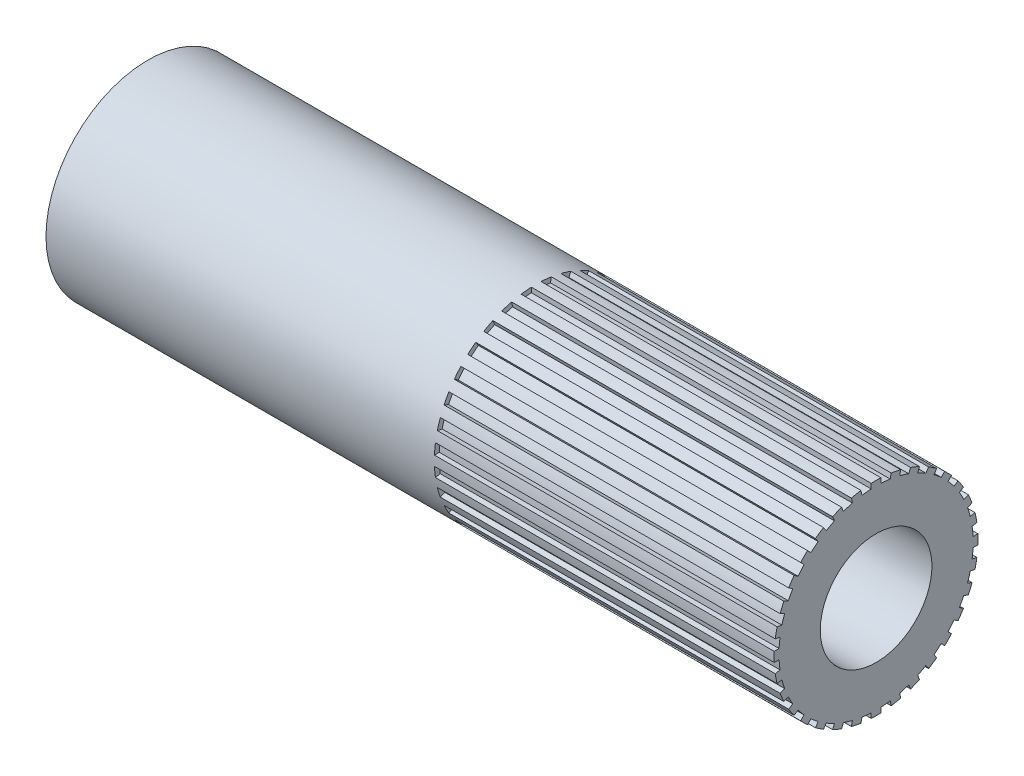
SolidWorks part; units mm, degrees
material "AISI 1020"
ref_plane "Front Plane" through (0, 0, 0) normal (0, 0, 1) x (1, 0, 0)
ref_plane "Top Plane" through (0, 0, 0) normal (0, 1, 0) x (1, 0, 0)
ref_plane "Right Plane" through (0, 0, 0) normal (1, 0, 0) x (0, 0, -1)
sketch "Sketch1" plane through (0, 0, 0) normal (0, 1, 0) x (1, 0, 0)
  line L0 (-77.5, 0) -> (77.5, 0) construction
  line L2 (-77.5, 0) -> (-77.5, -16)
  line L3 (-77.5, -16) -> (77.5, -16)
  line L4 (77.5, 0) -> (77.5, -16)
  line L5 (0, 0) -> (77.5, -16) construction
  line L6 (-77.5, -16) -> (0, 0) construction
  line L7 (-77.5, 0) -> (77.5, 0)
  point P0 (0, 0)
  point P2 (0, 0)
  dimension "D1" = 155
  dimension "D2" = 16
revolve "Revolve1" add sketch "Sketch1" angle 360 about L7
sketch "Sketch2" plane through (0, 0, 0) normal (0, 1, 0) x (1, 0, 0)
  line L1 (-77.5, 16) -> (-77.5, -16) construction
  circle A0 centre (-53.5, 0) radius 6.25
  dimension "D1" = 12.5
  dimension "D2" = 24
extrude "Cut-Extrude1" cut sketch "Sketch2" against normal through all both and the other way through all
sketch "Sketch4" plane through (-77.5, 0, 0) normal (-1, 0, 0) x (0, 0, 1)
  line L1 (-25, 3.5) -> (25, 3.5)
  line L2 (-25, 3.5) -> (-25, -3.5)
  line L3 (-25, -3.5) -> (25, -3.5)
  line L4 (25, 3.5) -> (25, -3.5)
  line L5 (-25, 3.5) -> (25, -3.5) construction
  line L6 (-25, -3.5) -> (25, 3.5) construction
  point P0 (0, 0)
  dimension "D1" = 7
  dimension "D2" = 50
extrude "Cut-Extrude3" cut sketch "Sketch4" against normal blind 38
sketch "Sketch6" plane through (-77.5, 0, 0) normal (-1, 0, 0) x (0, 0, 1)
  line L1 (-15.6125, 3.5) -> (15.6125, 3.5)
  line L2 (-15.6125, 3.5) -> (15.6125, 3.5)
  line L3 (15.6125, -3.5) -> (-15.6125, -3.5)
  line L4 (15.6125, -3.5) -> (-15.6125, -3.5)
  arc A1 (15.6125, 3.5) -> (-15.6125, 3.5) centre (0, 0) ccw
  arc A2 (15.6125, 3.5) -> (-15.6125, 3.5) centre (0, 0) ccw
  arc A3 (-15.6125, -3.5) -> (15.6125, -3.5) centre (0, 0) ccw
  arc A4 (-15.6125, -3.5) -> (15.6125, -3.5) centre (0, 0) ccw
  dimension "D1" = 0
  dimension "D2" = 0
extrude "Boss-Extrude1" add sketch "Sketch6" along normal blind 5
sketch "Sketch7" plane through (-82.5, 0, 0) normal (-1, 0, 0) x (0, 0, 1)
  point P0 (0, 0)
hole_wizard "Ø24.0 (24) Diameter Hole1" positions "Sketch10" profile "Sketch11" hole size "Ø24.0" standard "ANSI Metric"
sketch "Sketch10" plane through (-82.5, 0, 0) normal (-1, 0, 0) x (0, 0, 1)
  point P0 (0, 0)
sketch "Sketch11" plane through (-82.5, 0, 0) normal (0, 1, 0) x (0, 0, 1)
  line L0 (0, 0) -> (0, 27.2103)
  line L1 (0, 27.2103) -> (12, 20)
  line L2 (12, 20) -> (12, 0)
  line L5 (12, 0) -> (0, 0)
  line L10 (0, 27.2103) -> (-12, 20) construction
  line L11 (0, -6.35) -> (0, 107.95) construction
  dimension "Hole Dia." = 24
  dimension "Hole Depth" = 20
  dimension "Drill Angle" = 118
sketch "Sketch24" plane through (-82.5, 0, 0) normal (-1, 0, 0) x (0, 0, 1)
  circle A0 centre (0, 0) radius 12
  dimension "D1" = 24
extrude "Cut-Extrude12" cut sketch "Sketch24" against normal blind 20
sketch "Sketch12" plane through (77.5, 0, 0) normal (1, 0, 0) x (0, 0, -1)
  circle A0 centre (0, 0) radius 16 construction
  circle A1 centre (0, 0) radius 16
  circle A2 centre (0, 0) radius 10
  dimension "D1" = 20
extrude "Cut-Extrude6" cut sketch "Sketch12" against normal blind 35
sketch "Sketch13" plane through (77.5, 0, 0) normal (1, 0, 0) x (0, 0, -1)
  circle A0 centre (0, 0) radius 6
  dimension "D1" = 12
extrude "Boss-Extrude2" add sketch "Sketch13" along normal blind 15
sketch "Sketch14" plane through (77.5, 0, 0) normal (1, 0, 0) x (0, 0, -1)
  line L1 (-0.5, 10.5) -> (0.5, 10.5)
  line L2 (-0.5, 10.5) -> (-0.5, 9.5)
  line L3 (-0.5, 9.5) -> (0.5, 9.5)
  line L4 (0.5, 10.5) -> (0.5, 9.5)
  line L5 (-0.5, 10.5) -> (0.5, 9.5) construction
  line L6 (-0.5, 9.5) -> (0.5, 10.5) construction
  circle A0 centre (0, 0) radius 10 construction
  point P0 (0, 10)
  dimension "D1" = 1
  dimension "D2" = 1
chamfer "Chamfer2" distance 0.5 angle 45 1 edges at (92.5, 0, -6)
ref_plane "Plane1" through (47.5, 0, 0) normal (1, 0, 0) x (0, 0, -1)
sketch "Sketch17" plane through (47.5, 0, 0) normal (1, 0, 0) x (0, 0, -1)
  circle A0 centre (0, 0) radius 12.5
  circle A1 centre (0, 0) radius 16 construction
  circle A2 centre (0, 0) radius 16
  dimension "D1" = 25
extrude "Cut-Extrude9" cut sketch "Sketch17" against normal blind 75
sketch "Sketch19" plane through (0, 0, 0) normal (0, 1, 0) x (1, 0, 0)
  line L0 (-27.5, 16) -> (42.5, 12.5)
  line L1 (42.5, 12.5) -> (42.5, 0)
  line L2 (42.5, -10) -> (42.5, 10) construction
  line L3 (42.5, 0) -> (-27.5, 0)
  line L4 (-27.5, -16) -> (-27.5, 16) construction
  line L5 (-27.5, 0) -> (-27.5, 16)
extrude "Boss-Extrude3" add sketch "Sketch14" against normal blind 35
pattern_circular "CirPattern1" count 32 over 360 about axis through (0, 0, 0) along (1, 0, 0) of "Boss-Extrude3"
sketch "Sketch25" plane through (92.5, 0, 0) normal (1, 0, 0) x (0, 0, -1)
  circle A0 centre (0, 0) radius 5.75
  dimension "D1" = 11.5
extrude "Cut-Extrude13" cut sketch "Sketch25" against normal through all
sketch "Sketch26" plane through (0, 0, 0) normal (0, 1, 0) x (1, 0, 0)
  line L1 (77.5, 10.3958) -> (97.3017, 10.3958)
  line L2 (77.5, 10.3958) -> (77.5, -11.9643)
  line L3 (77.5, -11.9643) -> (97.3017, -11.9643)
  line L4 (97.3017, 10.3958) -> (97.3017, -11.9643)
  line L5 (-17.775, 22.7413) -> (-92.1182, 22.7413)
  line L6 (-17.775, 22.7413) -> (-17.775, -23.6547)
  line L7 (-17.775, -23.6547) -> (-92.1182, -23.6547)
  line L8 (-92.1182, 22.7413) -> (-92.1182, -23.6547)
extrude "Cut-Extrude14" cut sketch "Sketch26" against normal through all both and the other way through all
sketch "Sketch27" plane through (42.5, 0, 0) normal (1, 0, 0) x (0, 0, -1)
  circle A0 centre (0, 0) radius 10.5
extrude "Cut-Extrude16" cut sketch "Sketch27" against normal through all both and the other way through all flip side to cut
sketch "Sketch28" plane through (0, 0, 0) normal (0, 1, 0) x (1, 0, 0)
  line L0 (-17.775, -10.5) -> (77.5, -10.5) construction
  line L1 (77.5, 10.5) -> (2.5, 10.5)
  line L2 (77.5, 10.5) -> (77.5, -10.5)
  line L3 (77.5, -10.5) -> (2.5, -10.5)
  line L4 (2.5, 10.5) -> (2.5, -10.5)
  point P7 (78.0353, 11.5626)
  dimension "D1" = 75
extrude "Cut-Extrude17" cut sketch "Sketch28" against normal through all both and the other way through all flip side to cut
